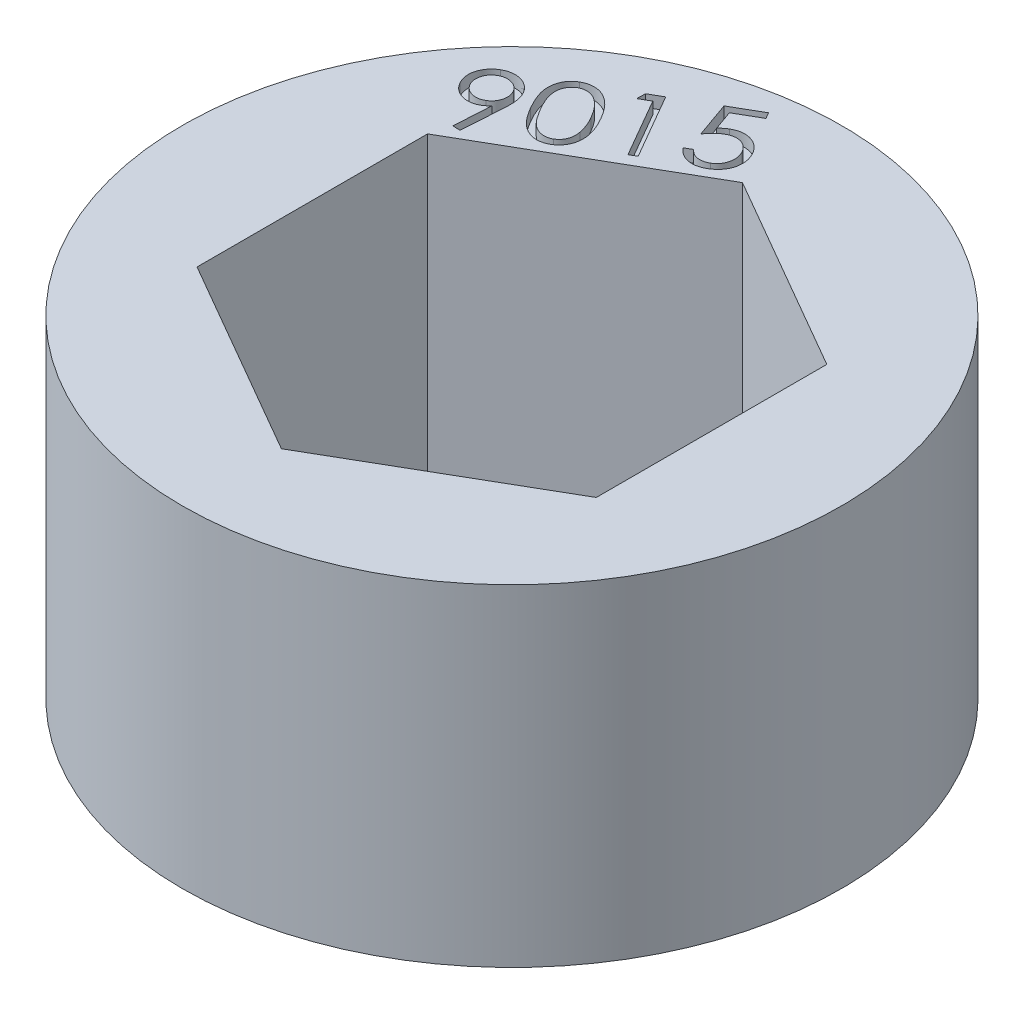
SolidWorks part; units mm, degrees
material "ABS"
ref_plane "Front Plane" through (0, 0, 0) normal (0, 0, 1) x (1, 0, 0)
ref_plane "Top Plane" through (0, 0, 0) normal (0, 1, 0) x (1, 0, 0)
ref_plane "Right Plane" through (0, 0, 0) normal (1, 0, 0) x (0, 0, -1)
sketch "Sketch1" plane through (0, 0, 0) normal (0, 1, 0) x (1, 0, 0)
  line L1 (0, 7.7723) -> (-6.731, 3.8861)
  line L2 (-6.731, 3.8861) -> (-6.731, -3.8861)
  line L3 (-6.731, -3.8861) -> (0, -7.7723)
  line L4 (0, -7.7723) -> (6.731, -3.8861)
  line L5 (6.731, -3.8861) -> (6.731, 3.8861)
  line L6 (6.731, 3.8861) -> (0, 7.7723)
  circle A0 centre (0, 0) radius 11.1125
  circle A1 centre (0, 0) radius 6.731 construction
  dimension "D1" = 22.225
  dimension "D2" = 13.462
extrude "Boss-Extrude1" add sketch "Sketch1" along normal blind 11.176
sketch "Sketch2" plane through (0, 11.176, 0) normal (0, 1, 0) x (1, 0, 0)
  line L0 (-6.909, 4.2527) -> (-0.2563, 8.0936) construction
  line L1 (0, 7.7723) -> (-6.731, 3.8861) construction
  text T0 "9015\r\n" font "Century Gothic" height 2.54
  dimension "D1" = 0.4064
extrude "Cut-Extrude1" cut sketch "Sketch2" against normal blind 0.4
